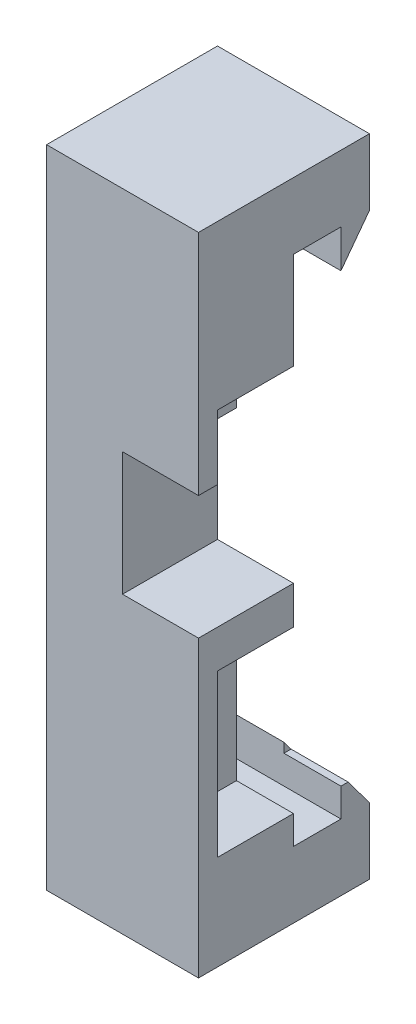
SolidWorks part; units mm, degrees
ref_plane "Front Plane" through (0, 0, 0) normal (0, 0, 1) x (1, 0, 0)
ref_plane "Top Plane" through (0, 0, 0) normal (0, 1, 0) x (1, 0, 0)
ref_plane "Right Plane" through (0, 0, 0) normal (1, 0, 0) x (0, 0, -1)
sketch "Sketch1" plane through (0, 0, 0) normal (0, 0, 1) x (1, 0, 0)
  line L1 (0, 0) -> (4, 0)
  line L2 (0, 0) -> (0, 17)
  line L3 (0, 17) -> (4, 17)
  line L4 (4, 0) -> (4, 17)
  dimension "D1" = 17
  dimension "D2" = 4
extrude "Boss-Extrude1" add sketch "Sketch1" along normal blind 6
sketch "Sketch2" plane through (0, 0, 6) normal (0, 0, 1) x (1, 0, 0)
  line L0 (4, 0) -> (4, 17) construction
  line L1 (4, 11) -> (2, 11)
  line L2 (4, 11) -> (4, 7.75)
  line L3 (4, 7.75) -> (2, 7.75)
  line L4 (2, 11) -> (2, 7.75)
  line L5 (4, 17) -> (0, 17) construction
  line L6 (0, 0) -> (4, 0) construction
  line L7 (0, 17) -> (0, 0) construction
  line L9 (4, 3.75) -> (2.5, 3.75)
  line L10 (4, 3.75) -> (4, 2.5)
  line L11 (4, 2.5) -> (2.5, 2.5)
  line L12 (2.5, 3.75) -> (2.5, 2.5)
  point P6 (3, 11)
  point P17 (0, 0)
  point P18 (0, 0)
  dimension "D1" = 6
  dimension "D3" = 2
  dimension "D4" = 1.5
  dimension "D5" = 2.5
  dimension "D6" = 4
  dimension "D7" = 1.25
  dimension "D8" = 3.25
extrude "Cut-Extrude1" cut sketch "Sketch2" against normal through all
sketch "Sketch3" plane through (0, 0, 0) normal (-1, 0, 0) x (0, 0, 1)
  line L0 (0, 15.25) -> (0.75, 14.25)
  line L1 (0, 17) -> (0, 0) construction
  line L2 (0.75, 14.25) -> (0.75, 15.25)
  line L3 (0.75, 15.25) -> (2, 15.25)
  line L4 (2, 15.25) -> (2, 1.75)
  line L5 (0, 15.25) -> (0, 1.75)
  line L6 (-999.8573, 8.5) -> (49000.1427, 8.5) construction
  line L7 (6, 17) -> (0, 17) construction
  line L8 (6, 17) -> (6, 0) construction
  line L9 (0.75, 1.75) -> (2, 1.75)
  line L10 (0.75, 2.75) -> (0.75, 1.75)
  line L11 (0, 1.75) -> (0.75, 2.75)
  point P17 (0, 8.5)
  point P18 (2, 8.5)
  dimension "D1" = 1.75
  dimension "D2" = 4
  dimension "D3" = 1.25
  dimension "D4" = 1.75
  dimension "D5" = 1
extrude "Cut-Extrude2" cut sketch "Sketch3" against normal through all
sketch "Sketch4" plane through (4, 0, 0) normal (1, 0, 0) x (0, 0, -1)
  line L0 (-2, 2.5) -> (-6, 2.5) construction
  line L1 (-6, 3.75) -> (-4, 3.75)
  line L2 (-6, 3.75) -> (-6, 2.5)
  line L3 (-6, 2.5) -> (-4, 2.5)
  line L4 (-4, 3.75) -> (-4, 2.5)
  dimension "D1" = 2
extrude "Boss-Extrude2" add sketch "Sketch4" against normal blind 2
sketch "Sketch5" plane through (0, 0, 6) normal (0, 0, 1) x (1, 0, 0)
  line L0 (0, 17) -> (0, 0) construction
  line L1 (0, 14.5) -> (2, 14.5)
  line L2 (0, 14.5) -> (0, 2.5)
  line L3 (0, 2.5) -> (2, 2.5)
  line L4 (2, 14.5) -> (2, 2.5) construction
  line L5 (0, 0) -> (4, 0) construction
  line L6 (4, 17) -> (0, 17) construction
  line L7 (2, 12.2) -> (4, 12.2)
  line L8 (4, 11) -> (4, 17) construction
  line L9 (4, 12.2) -> (4, 11)
  line L10 (4, 11) -> (2, 11)
  line L11 (2, 11) -> (2, 7.75)
  line L12 (2, 7.75) -> (4, 7.75)
  line L13 (4, 7.75) -> (4, 6.55)
  line L14 (4, 0) -> (4, 7.75) construction
  line L15 (4, 6.55) -> (2, 6.55)
  line L16 (2, 6.55) -> (2, 2.5)
  line L17 (2, 14.5) -> (2, 12.2)
  point P6 (1, 2.5)
  dimension "D1" = 2.5
  dimension "D2" = 2.5
  dimension "D3" = 2
  dimension "D4" = 1.2
  dimension "D5" = 1.2
extrude "Boss-Extrude3" add sketch "Sketch5" along normal blind 2
sketch "Sketch6" plane through (0, 0, 2) normal (0, 0, -1) x (-1, 0, 0)
  line L1 (-4, 11) -> (-2.5, 11)
  line L2 (-4, 11) -> (-4, 12.7)
  line L3 (-4, 12.7) -> (-2.5, 12.7)
  line L4 (-2.5, 11) -> (-2.5, 12.7)
  line L5 (-2.5, 3.75) -> (-4, 3.75)
  line L6 (-2.5, 3.75) -> (-2.5, 7.75)
  line L7 (-2.5, 7.75) -> (-4, 7.75)
  line L8 (-4, 3.75) -> (-4, 7.75)
  dimension "D1" = 1.5
  dimension "D2" = 1.7
extrude "Cut-Extrude3" cut sketch "Sketch6" against normal blind 2
sketch "Sketch7" plane through (4, 0, 0) normal (1, 0, 0) x (0, 0, -1)
  line L0 (-6, 17) -> (0, 17) construction
  line L1 (-4.5, 17) -> (-8.5, 17)
  line L2 (-4.5, 17) -> (-4.5, 0)
  line L3 (-4.5, 0) -> (-8.5, 0)
  line L4 (-8.5, 17) -> (-8.5, 0)
  line L5 (-4, 7.75) -> (-4, 2.5) construction
  dimension "D1" = 0.5
  dimension "D2" = 4
extrude "Cut-Extrude4" cut sketch "Sketch7" against normal blind 10
sketch "Sketch8" plane through (0, 0, 4) normal (0, 0, -1) x (-1, 0, 0)
  line L0 (-4, 2.5) -> (-4, 7.75) construction
  line L1 (-2.5, 7.75) -> (-4, 7.75)
  line L2 (-2.5, 7.75) -> (-2.5, 6.75)
  line L3 (-2.5, 6.75) -> (-4, 6.75)
  line L4 (-4, 7.75) -> (-4, 6.75)
  dimension "D1" = 1
extrude "Boss-Extrude4" add sketch "Sketch8" along normal up to surface (2 mm away) up to face at (2.5, 8.4917, 2)
